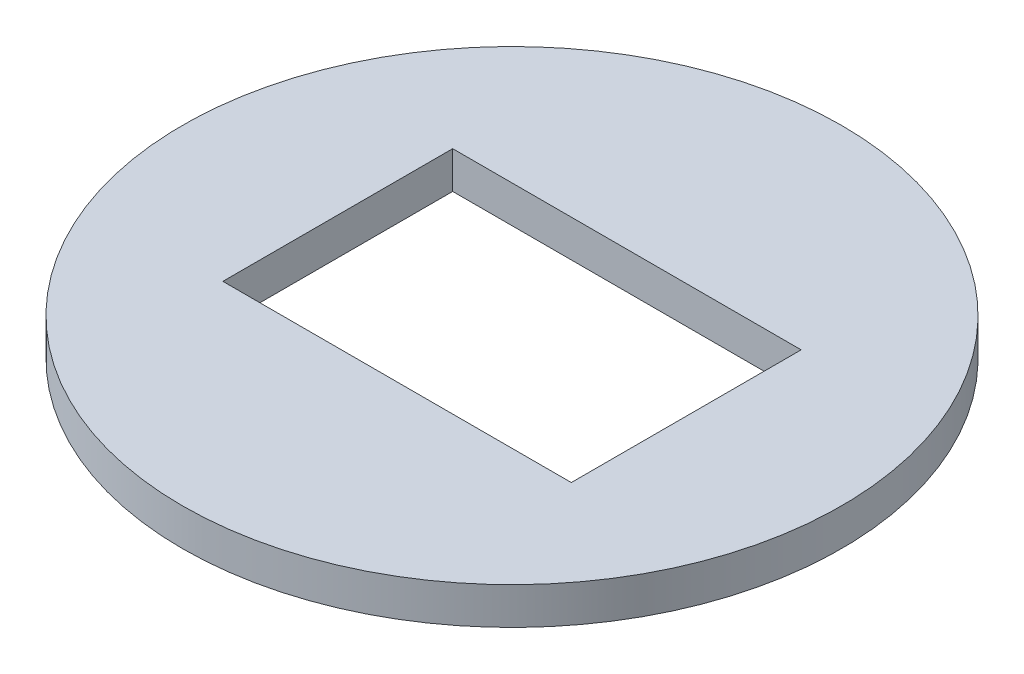
SolidWorks part; units mm, degrees
ref_plane "Front Plane" through (0, 0, 0) normal (0, 0, 1) x (1, 0, 0)
ref_plane "Top Plane" through (0, 0, 0) normal (0, 1, 0) x (1, 0, 0)
ref_plane "Right Plane" through (0, 0, 0) normal (1, 0, 0) x (0, 0, -1)
sketch "Sketch1" plane through (0, 0, 0) normal (0, 1, 0) x (1, 0, 0)
  circle A0 centre (0, 0) radius 88.9
  dimension "D1" = 177.8
extrude "Boss-Extrude1" add sketch "Sketch1" along normal blind 10
extrude "Cut-Extrude3" cut sketch "Sketch4" against normal blind 30
sketch "Sketch4" plane through (0, -20, 0) normal (0, -1, 0) x (1, 0, 0)
  line L1 (-47, 31) -> (47, 31)
  line L2 (-47, 31) -> (-47, -31)
  line L3 (-47, -31) -> (47, -31)
  line L4 (47, 31) -> (47, -31)
  line L5 (-47, 31) -> (47, -31) construction
  line L6 (-47, -31) -> (47, 31) construction
  point P0 (0, 0)
